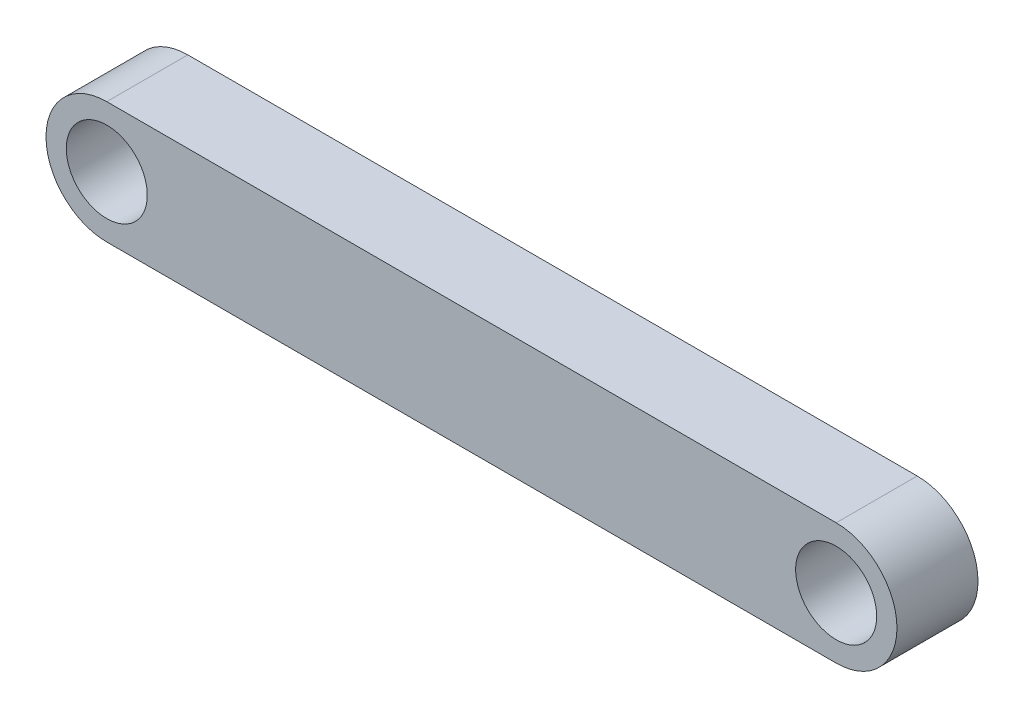
SolidWorks part; units mm, degrees
ref_plane "Front Plane" through (0, 0, 0) normal (0, 0, 1) x (1, 0, 0)
ref_plane "Top Plane" through (0, 0, 0) normal (0, 1, 0) x (1, 0, 0)
ref_plane "Right Plane" through (0, 0, 0) normal (1, 0, 0) x (0, 0, -1)
sketch "Sketch1" plane through (0, 0, 0) normal (0, 0, 1) x (1, 0, 0)
  line L0 (-36, 3) -> (0, 3)
  line L1 (-36, -3) -> (0, -3)
  line L2 (-18, -3) -> (-18, 3) construction
  line L3 (-36, 3) -> (-36, -3) construction
  line L4 (0, 3) -> (0, -3) construction
  arc A0 (0, -3) -> (0, 3) centre (0, 0) ccw
  circle A1 centre (0, 0) radius 2
  circle A2 centre (-36, 0) radius 2
  arc A3 (-36, -3) -> (-36, 3) centre (-36, 0) cw
  point P15 (-36, 0)
  point P16 (0, 0)
  dimension "D1" = 4
  dimension "D2" = 6
  dimension "D3" = 36
extrude "Boss-Extrude1" add sketch "Sketch1" along normal blind 4
